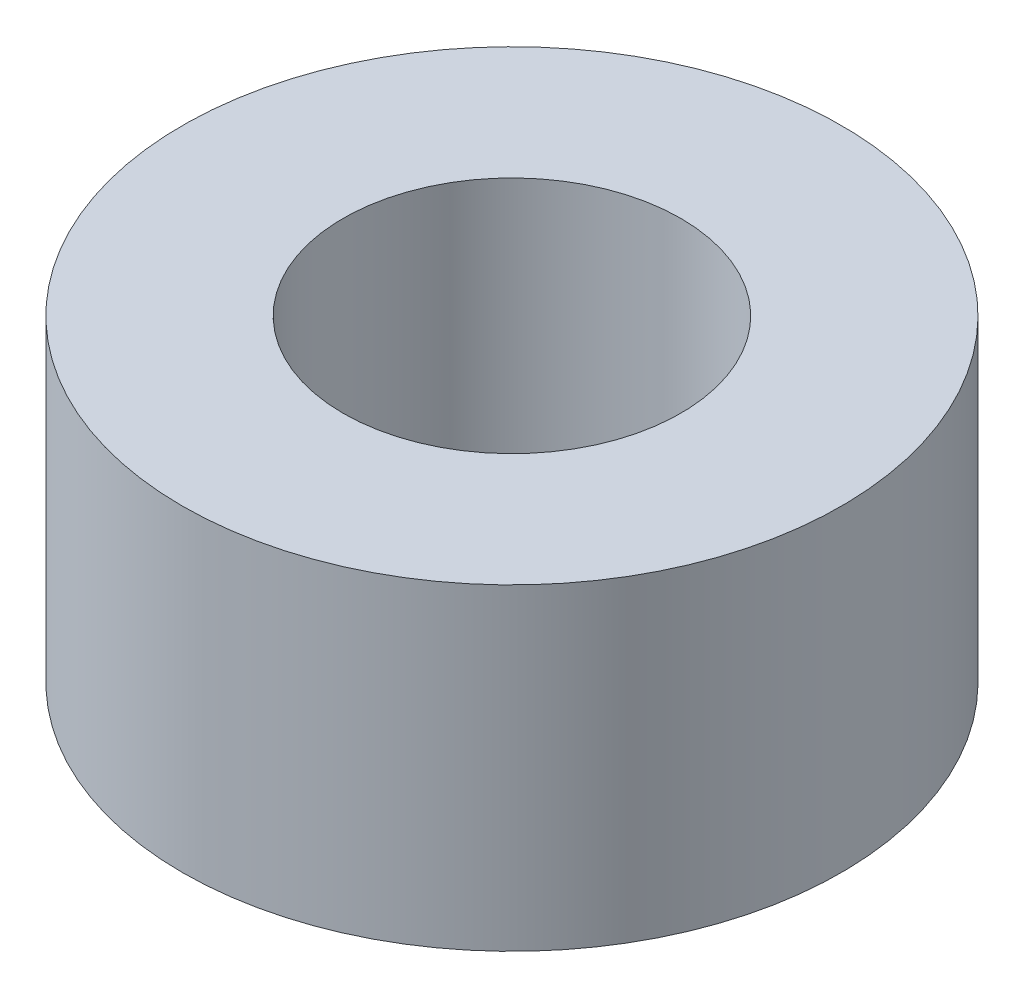
SolidWorks part; units mm, degrees
ref_plane "Ebene vorne" through (0, 0, 0) normal (0, 0, 1) x (1, 0, 0)
ref_plane "Ebene oben" through (0, 0, 0) normal (0, 1, 0) x (1, 0, 0)
ref_plane "Ebene rechts" through (0, 0, 0) normal (1, 0, 0) x (0, 0, -1)
sketch "Skizze2" plane through (0, 0, 0) normal (0, 1, 0) x (1, 0, 0)
  circle A0 centre (0, 0) radius 4.05
  dimension "D1" = 8.1
extrude "Aufsatz-Linear austragen1" add sketch "Skizze2" along normal blind 3.9
sketch "Skizze3" plane through (0, 0, 0) normal (0, -1, 0) x (1, 0, 0)
  circle A0 centre (0, 0) radius 2.075
  dimension "D1" = 4.15
extrude "Schnitt-Linear austragen1" cut sketch "Skizze3" against normal blind 3.9
